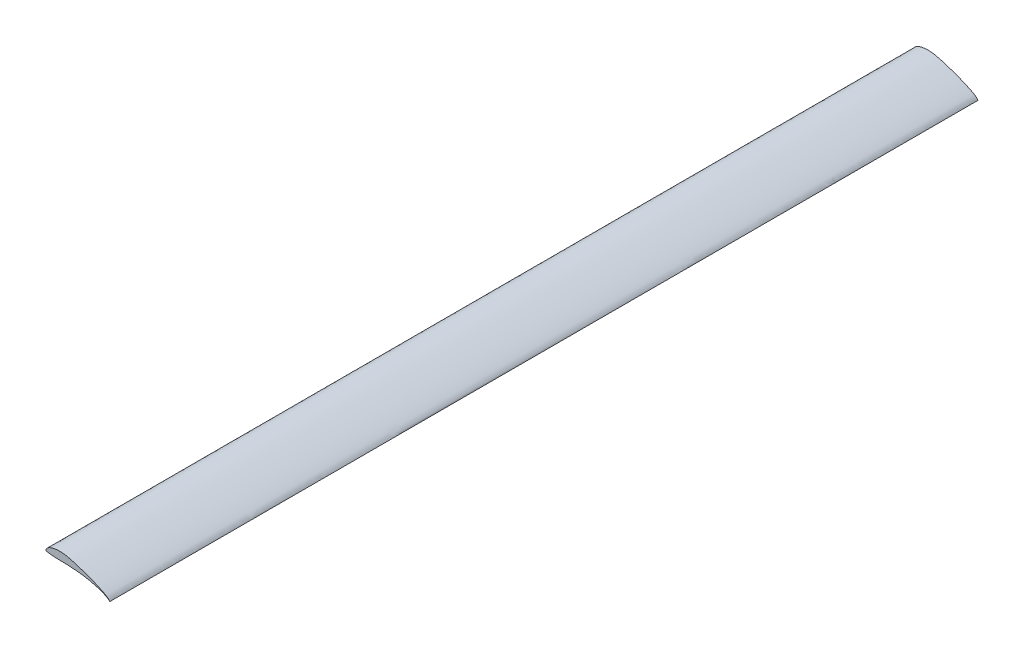
SolidWorks part; units mm, degrees
ref_plane "Front Plane" through (0, 0, 0) normal (0, 0, 1) x (1, 0, 0)
ref_plane "Top Plane" through (0, 0, 0) normal (0, 1, 0) x (1, 0, 0)
ref_plane "Right Plane" through (0, 0, 0) normal (1, 0, 0) x (0, 0, -1)
curve "Curve1"
  spline degree 3 poles (0.9961, 0.0026, 0) (1.0009, -0.0006, 0) (0.9967, 0.0025, 0) (0.9939, 0.0052, 0) (0.9878, 0.0109, 0) (0.9805, 0.017, 0) (0.9705, 0.0231, 0) (0.9581, 0.029, 0) (0.9432, 0.0352, 0) (0.9257, 0.0415, 0) (0.9057, 0.048, 0) (0.8834, 0.0546, 0) (0.8588, 0.0611, 0) (0.8322, 0.0677, 0) (0.8036, 0.0742, 0) (0.7732, 0.0806, 0) (0.7412, 0.0869, 0) (0.7079, 0.0929, 0) (0.6733, 0.0987, 0) (0.6378, 0.1042, 0) (0.6014, 0.1094, 0) (0.5646, 0.1143, 0) (0.5275, 0.1189, 0) (0.4904, 0.1231, 0) (0.4536, 0.1269, 0) (0.4175, 0.1302, 0) (0.3823, 0.1328, 0) (0.3482, 0.1346, 0) (0.3154, 0.1354, 0) (0.284, 0.1353, 0) (0.2541, 0.1338, 0) (0.2258, 0.1307, 0) (0.1988, 0.1263, 0) (0.1732, 0.1206, 0) (0.1489, 0.1139, 0) (0.1262, 0.1063, 0) (0.1051, 0.0981, 0) (0.0858, 0.0892, 0) (0.0682, 0.0798, 0) (0.0525, 0.0701, 0) (0.0388, 0.0602, 0) (0.0271, 0.0502, 0) (0.0176, 0.0401, 0) (0.0103, 0.03, 0) (0.0049, 0.0202, 0) (0.0014, 0.0108, 0) (-0.0002, 0.0022, 0) (0.0001, -0.0051, 0) (0.002, -0.0118, 0) (0.0089, -0.0151, 0) (0.0183, -0.0156, 0) (0.0312, -0.016, 0) (0.0473, -0.0153, 0) (0.0666, -0.0141, 0) (0.0888, -0.012, 0) (0.1137, -0.0092, 0) (0.1411, -0.0057, 0) (0.1711, -0.0007, 0) (0.2038, 0.0055, 0) (0.2393, 0.0123, 0) (0.2775, 0.0195, 0) (0.3182, 0.0267, 0) (0.361, 0.0338, 0) (0.4056, 0.0404, 0) (0.4517, 0.0464, 0) (0.4987, 0.0515, 0) (0.5464, 0.0555, 0) (0.5941, 0.0584, 0) (0.6414, 0.06, 0) (0.6878, 0.0602, 0) (0.7328, 0.059, 0) (0.7758, 0.0564, 0) (0.8164, 0.0525, 0) (0.854, 0.0475, 0) (0.8881, 0.0414, 0) (0.9184, 0.0345, 0) (0.9444, 0.027, 0) (0.9656, 0.0191, 0) (0.9807, 0.0119, 0) (0.9918, 0.0052, 0) (0.9961, 0.0026, 0) (1.0009, -0.0006, 0) (0.9967, 0.0025, 0) knots -0.009748 -0.004147 -0.001 0 0.00098 0.003649 0.007483 0.012095 0.017526 0.024052 0.031783 0.040678 0.05071 0.061833 0.073989 0.087118 0.101145 0.115991 0.13157 0.147788 0.164551 0.181758 0.199312 0.217095 0.23499 0.252857 0.270541 0.287887 0.304773 0.321101 0.336806 0.3518 0.366031 0.379616 0.392653 0.40517 0.417172 0.428604 0.439419 0.449597 0.459102 0.467908 0.475988 0.483309 0.489875 0.495803 0.501149 0.505903 0.510047 0.513579 0.516447 0.51935 0.523823 0.529974 0.537716 0.546968 0.557637 0.56962 0.582804 0.597247 0.613135 0.630444 0.649056 0.668822 0.689595 0.71119 0.733427 0.756094 0.778989 0.80189 0.824567 0.846792 0.868338 0.888978 0.908492 0.926659 0.943286 0.958169 0.971136 0.981956 0.990252 0.995853 0.999 1 1.00098 1.003649 1.007483 periodic
sketch "Sketch1" plane through (0, 0, 0) normal (0, 0, 1) x (1, 0, 0)
  line L0 (15.6074, -1.5683) -> (0.9147, 1.4524) construction
  line L1 (0.9147, 1.4524) -> (1.1567, 2.6296) construction
  spline S1 degree 3 poles (15.5584, -1.5184) (15.6187, -1.5805) (15.5666, -1.522) (15.534, -1.4735) (15.4606, -1.3711) (15.3719, -1.26) (15.2441, -1.1401) (15.08, -1.0156) (14.879, -0.8796) (14.6411, -0.7333) (14.3674, -0.5777) (14.0593, -0.414) (13.7185, -0.2428) (13.3467, -0.0656) (12.9462, 0.1164) (12.5193, 0.3023) (12.0686, 0.4909) (11.5966, 0.6805) (11.1064, 0.8704) (10.6008, 1.0589) (10.083, 1.2455) (9.5563, 1.4287) (9.0248, 1.6077) (8.4928, 1.7819) (7.9645, 1.9489) (7.4441, 2.1067) (6.9347, 2.2518) (6.439, 2.3815) (5.959, 2.4923) (5.4977, 2.5861) (5.0542, 2.6539) (4.628, 2.694) (4.2182, 2.7109) (3.8247, 2.7046) (3.4488, 2.6796) (3.0924, 2.6373) (2.7575, 2.5801) (2.4461, 2.508) (2.1596, 2.4238) (1.8999, 2.3285) (1.6686, 2.2239) (1.4667, 2.113) (1.2962, 1.9938) (1.158, 1.8673) (1.0488, 1.739) (0.9696, 1.6122) (0.9192, 1.4904) (0.9018, 1.3823) (0.9092, 1.2783) (1.0017, 1.2084) (1.1382, 1.1731) (1.3255, 1.1276) (1.5649, 1.089) (1.852, 1.0495) (2.1841, 1.0124) (2.5579, 0.9779) (2.9717, 0.9472) (3.4272, 0.9295) (3.9262, 0.9222) (4.4688, 0.9144) (5.052, 0.904) (5.6713, 0.8874) (6.3216, 0.8615) (6.9973, 0.8239) (7.6919, 0.7721) (8.399, 0.7049) (9.1111, 0.6202) (9.821, 0.5179) (10.5211, 0.3978) (11.2035, 0.2603) (11.8606, 0.1068) (12.4848, -0.0609) (13.0688, -0.2407) (13.6058, -0.4289) (14.0891, -0.6218) (14.5135, -0.8153) (14.8717, -1.0027) (15.1593, -1.1831) (15.3596, -1.3353) (15.5032, -1.4674) (15.5584, -1.5184) (15.6187, -1.5805) (15.5666, -1.522) knots -0.009748 -0.004147 -0.001 0 0.00098 0.003649 0.007483 0.012095 0.017526 0.024052 0.031783 0.040678 0.05071 0.061833 0.073989 0.087118 0.101145 0.115991 0.13157 0.147788 0.164551 0.181758 0.199312 0.217095 0.23499 0.252857 0.270541 0.287887 0.304773 0.321101 0.336806 0.3518 0.366031 0.379616 0.392653 0.40517 0.417172 0.428604 0.439419 0.449597 0.459102 0.467908 0.475988 0.483309 0.489875 0.495803 0.501149 0.505903 0.510047 0.513579 0.516447 0.51935 0.523823 0.529974 0.537716 0.546968 0.557637 0.56962 0.582804 0.597247 0.613135 0.630444 0.649056 0.668822 0.689595 0.71119 0.733427 0.756094 0.778989 0.80189 0.824567 0.846792 0.868338 0.888978 0.908492 0.926659 0.943286 0.958169 0.971136 0.981956 0.990252 0.995853 0.999 1 1.00098 1.003649 1.007483 only from (15.6074, -1.5683) to (15.6074, -1.5683)
  dimension "D1" = 15
extrude "Boss-Extrude1" add sketch "Sketch1" along normal blind 200
